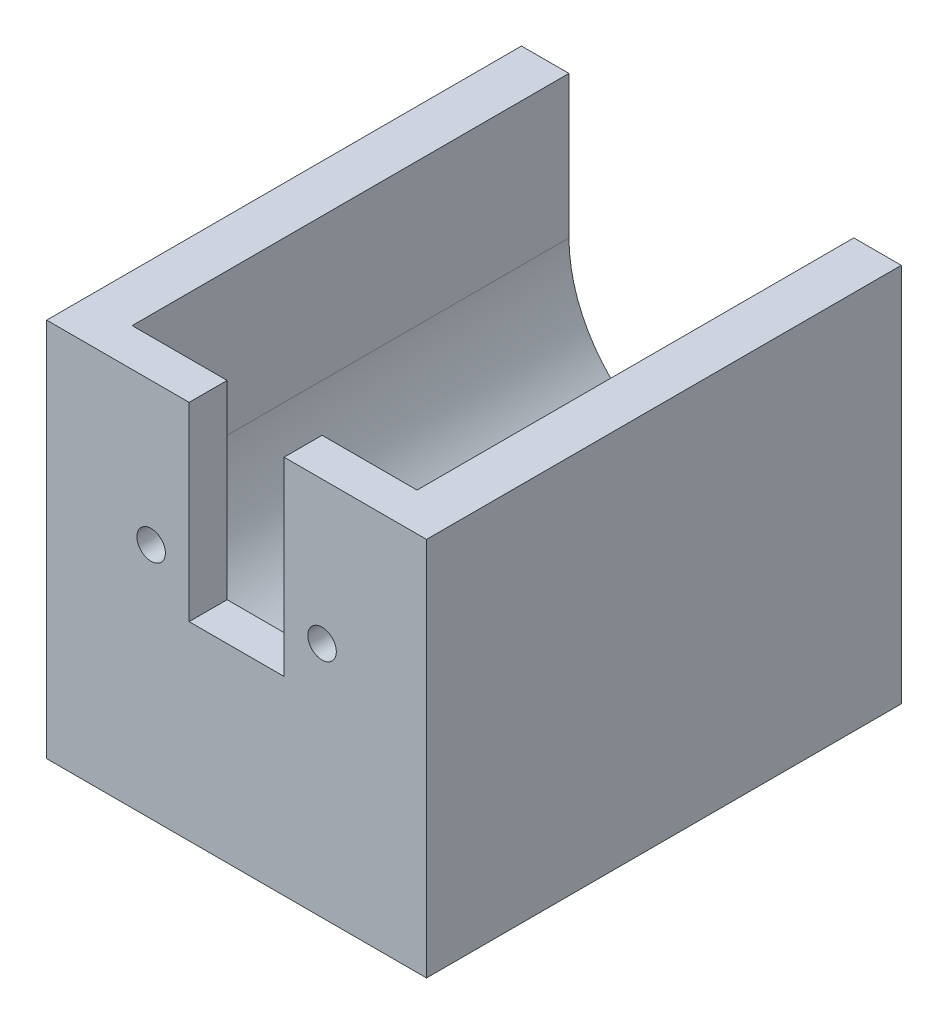
SolidWorks part; units mm, degrees
ref_plane "Ön Düzlem" through (0, 0, 0) normal (0, 0, 1) x (1, 0, 0)
ref_plane "Üst Düzlem" through (0, 0, 0) normal (0, 1, 0) x (1, 0, 0)
ref_plane "Sağ Düzlem" through (0, 0, 0) normal (1, 0, 0) x (0, 0, -1)
sketch "Çizim1" plane through (0, 0, 0) normal (0, 1, 0) x (1, 0, 0)
  line L1 (0, 0) -> (20, 0)
  line L2 (0, 0) -> (0, 25)
  line L3 (0, 25) -> (20, 25)
  line L4 (20, 0) -> (20, 25)
  dimension "D1" = 20
  dimension "D2" = 25
extrude "Yükseklik-Ekstrüzyon1" add sketch "Çizim1" along normal blind 20
sketch "Çizim2" plane through (0, 0, 0) normal (0, 0, 1) x (1, 0, 0)
  line L0 (0, 20) -> (20, 20) construction
  line L1 (2.5, 12.5) -> (2.5, 20)
  line L2 (2.5, 20) -> (17.5, 20)
  line L3 (17.5, 20) -> (17.5, 12.5)
  arc A0 (2.5, 12.5) -> (17.5, 12.5) centre (10, 12.5) ccw
  point P5 (10, 20)
  dimension "D1" = 15
extrude "Kes-Ekstrüzyon3" cut sketch "Çizim2" against normal blind 32
sketch "Çizim3" plane through (0, 20, 0) normal (0, 1, 0) x (1, 0, 0)
  line L0 (17.5, 25) -> (2.5, 25) construction
  circle A0 centre (10, 10) radius 3
  circle A1 centre (10, 19) radius 3
  point P4 (9.5379, 15.852)
  point P7 (10, 25)
  dimension "D1" = 6
  dimension "D2" = 6
  dimension "D3" = 6
  dimension "D4" = 9
extrude "Kes-Ekstrüzyon4" cut sketch "Çizim3" against normal blind 17
sketch "Çizim4" plane through (0, 0, 0) normal (0, 0, 1) x (1, 0, 0)
  line L0 (12.5, 20) -> (20, 20)
  line L1 (0, 20) -> (7.5, 20)
  line L2 (0, 20) -> (0, 0)
  line L3 (0, 0) -> (20, 0)
  line L4 (20, 20) -> (20, 0)
  line L5 (7.5, 10) -> (12.5, 10)
  line L6 (7.5, 10) -> (7.5, 20)
  line L8 (12.5, 10) -> (12.5, 20)
  line L9 (7.5, 10) -> (12.5, 20) construction
  line L10 (7.5, 20) -> (12.5, 10) construction
  point P6 (10, 15)
  point P11 (0, 0)
  point P12 (0, 0)
  point P13 (0, 0)
  point P14 (8.8411, 14.8817)
  point P15 (9.9043, 14.5421)
  point P16 (0, 0)
  point P17 (10.1464, 15)
  point P18 (10, 0)
  dimension "D1" = 10
  dimension "D2" = 5
extrude "Yükseklik-Ekstrüzyon2" add sketch "Çizim4" against normal blind 2
sketch "Çizim5" plane through (0, 0, -25) normal (0, 0, -1) x (-1, 0, 0)
  line L0 (-14.5, 12.5) -> (-5.5, 12.5) construction
  line L1 (-20, 0) -> (0, 0) construction
  circle A0 centre (-14.5, 12.5) radius 0.75
  circle A1 centre (-5.5, 12.5) radius 0.75
  arc A2 (-17.5, 12.5) -> (-2.5, 12.5) centre (-10, 12.5) ccw construction
  point P3 (-10, 12.5)
  point P7 (-10, 0)
  point P11 (-10, 5)
  dimension "D1" = 1.5
  dimension "D3" = 1.5
  dimension "D2" = 9
  dimension "D4" = 7.5
extrude "Kes-Ekstrüzyon5" cut sketch "Çizim5" against normal blind 32
